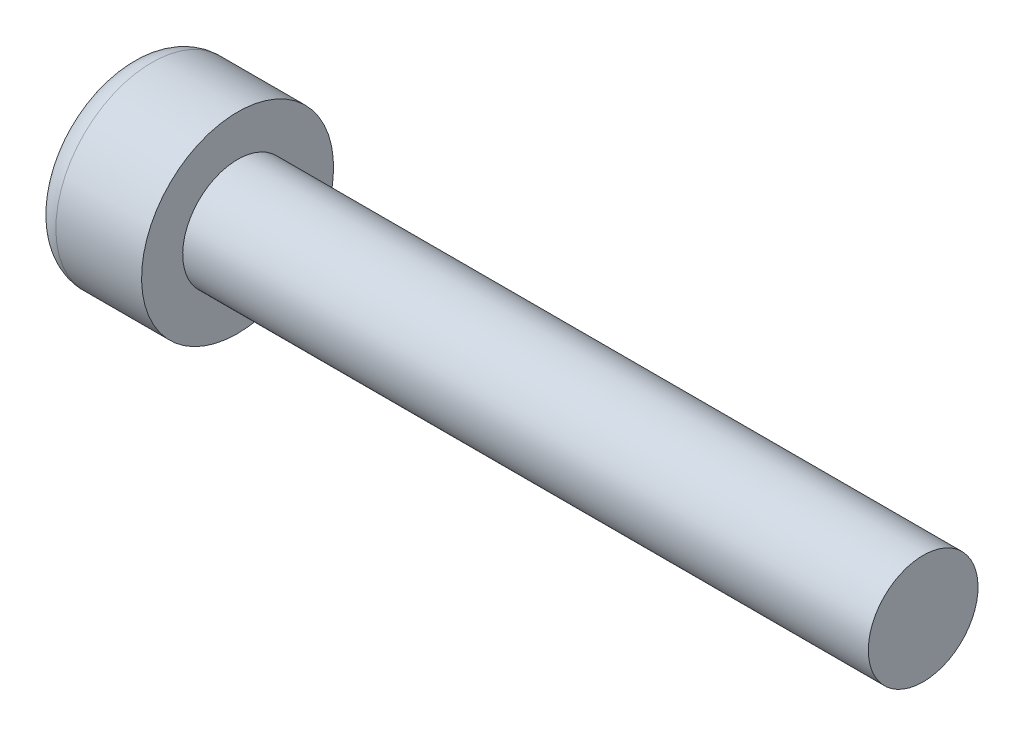
SolidWorks part; units mm, degrees
material "Plain Carbon Steel"
ref_plane "Front Plane" through (0, 0, 0) normal (0, 0, 1) x (1, 0, 0)
ref_plane "Top Plane" through (0, 0, 0) normal (0, 1, 0) x (1, 0, 0)
ref_plane "Right Plane" through (0, 0, 0) normal (1, 0, 0) x (0, 0, -1)
sketch "Sketch1" plane through (0, 0, 0) normal (0, 0, 1) x (1, 0, 0)
  line L0 (0, 0) -> (0, 2.625)
  line L1 (0.875, 3.5) -> (4, 3.5)
  line L2 (4, 3.5) -> (4, 2)
  line L3 (4, 2) -> (29, 2)
  line L4 (29, 2) -> (29, 0)
  line L5 (29, 0) -> (0, 0) construction
  line L6 (0.875, 2.625) -> (0.875, 1.75) construction
  line L7 (0.875, 1.75) -> (0.875, 0.875) construction
  line L8 (0.875, 0.875) -> (0.875, 0) construction
  line L9 (0.875, 3.5) -> (0.875, 2.625) construction
  line L10 (0, 0) -> (29, 0)
  arc A0 (0, 2.625) -> (0.875, 3.5) centre (0.875, 2.625) cw
  dimension "D1" = 4
  dimension "D2" = 7
  dimension "D3" = 4
  dimension "D4" = 25
revolve "Revolve1" add sketch "Sketch1" angle 360 about L10
sketch "Sketch2" plane through (0, 0, 0) normal (-1, 0, 0) x (0, 0, 1)
  line L1 (0, 1.7321) -> (-1.5, 0.866)
  line L2 (-1.5, 0.866) -> (-1.5, -0.866)
  line L3 (-1.5, -0.866) -> (0, -1.7321)
  line L4 (0, -1.7321) -> (1.5, -0.866)
  line L5 (1.5, -0.866) -> (1.5, 0.866)
  line L6 (1.5, 0.866) -> (0, 1.7321)
  circle A0 centre (0, 0) radius 1.5 construction
  dimension "D1" = 3
extrude "Cut-Extrude1" cut sketch "Sketch2" against normal blind 2
